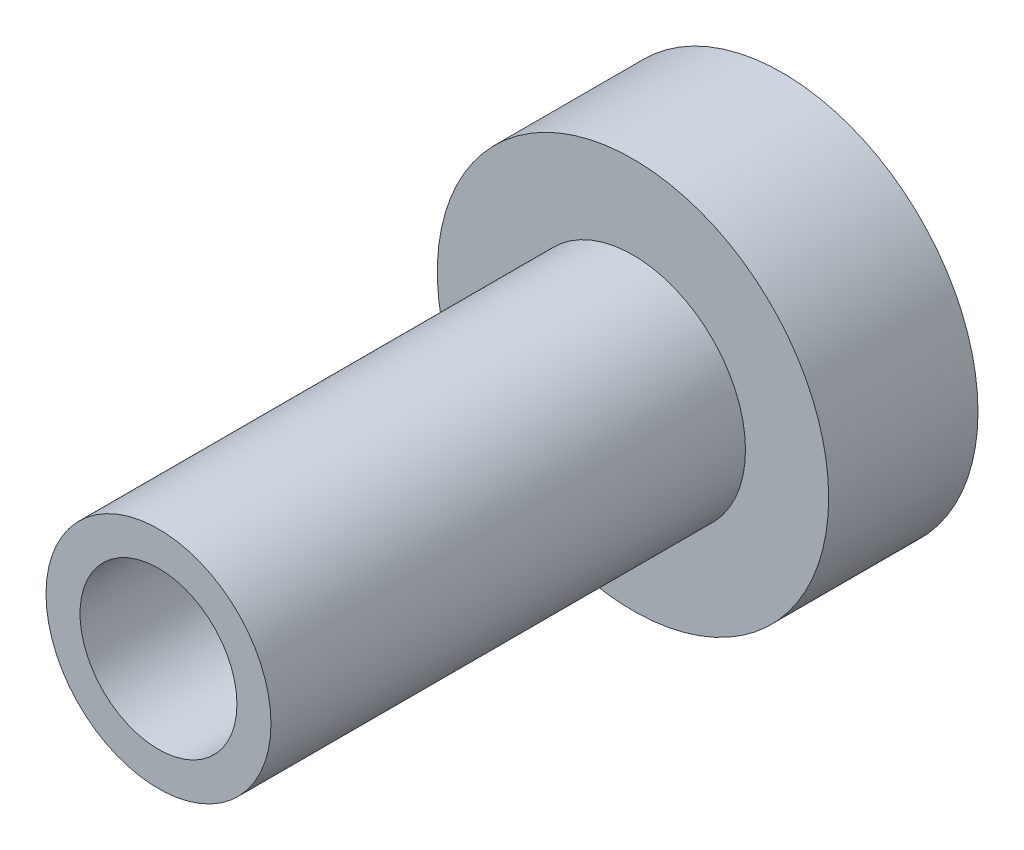
SolidWorks part; units mm, degrees
ref_plane "Front Plane" through (0, 0, 0) normal (0, 0, 1) x (1, 0, 0)
ref_plane "Top Plane" through (0, 0, 0) normal (0, 1, 0) x (1, 0, 0)
ref_plane "Right Plane" through (0, 0, 0) normal (1, 0, 0) x (0, 0, -1)
sketch "Sketch1" plane through (0, 0, 0) normal (0, 0, 1) x (1, 0, 0)
  circle A0 centre (0, 0) radius 10.35
  circle A1 centre (0, 0) radius 4.15
  dimension "D1" = 20.7
  dimension "D2" = 8.3
extrude "Boss-Extrude1" add sketch "Sketch1" along normal blind 33
sketch "Sketch2" plane through (0, 0, 33) normal (0, 0, 1) x (1, 0, 0)
  circle A0 centre (0, 0) radius 5.95
  circle A1 centre (0, 0) radius 10.35
  circle A2 centre (0, 0) radius 10.35 construction
  dimension "D1" = 11.9
extrude "Cut-Extrude1" cut sketch "Sketch2" against normal blind 25.1
